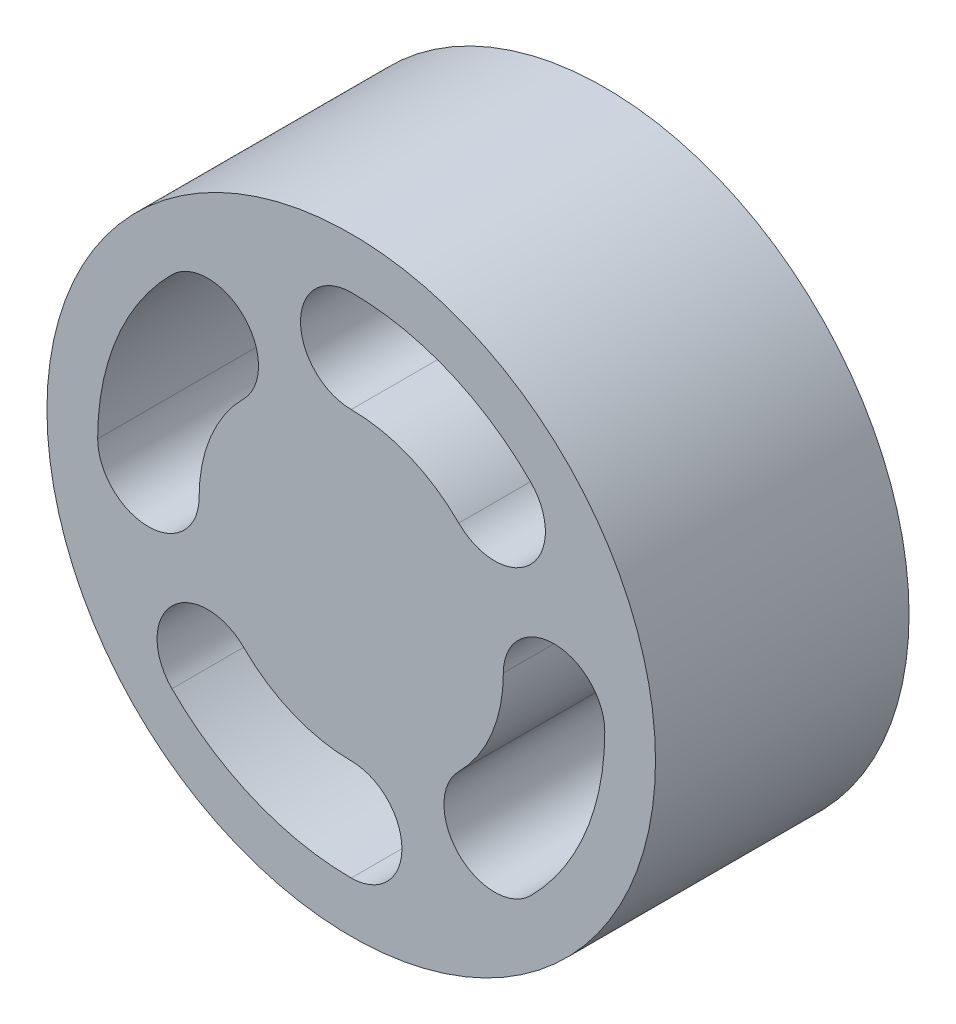
SolidWorks part; units mm, degrees
ref_plane "前视基准面" through (0, 0, 0) normal (0, 0, 1) x (1, 0, 0)
ref_plane "上视基准面" through (0, 0, 0) normal (0, 1, 0) x (1, 0, 0)
ref_plane "右视基准面" through (0, 0, 0) normal (1, 0, 0) x (0, 0, -1)
other "Configuration Table"
sketch "草图1" plane through (0, 0, 0) normal (0, 0, 1) x (1, 0, 0)
  circle A0 centre (0, 0) radius 30
  dimension "D1" = 60
extrude "凸台-拉伸1" add sketch "草图1" along normal blind 25
sketch "草图2" plane through (0, 0, 0) normal (0, 0, 1) x (1, 0, 0)
  line L0 (0, 0) -> (0, 1.4)
  line L1 (-1000, 1.4) -> (49000, 1.4)
  circle A0 centre (0, 0) radius 2
  circle A1 centre (0, 0) radius 3
  dimension "D1" = 4
  dimension "D2" = 6
  dimension "D3" = 1.4
extrude "凸台-拉伸5" add sketch "草图2" against normal blind 10 contours L1 A1 A0 | L1 A1 A0 | L1 A0
ref_plane "基准面1" through (0, 3, 0) normal (0, 1, 0) x (1, 0, 0)
sketch "草图4" plane through (0, 3, 0) normal (0, 1, 0) x (1, 0, 0)
  line L0 (-1.4283, 10) -> (1.4283, 10) construction
  circle A0 centre (0, 7) radius 1
  dimension "D1" = 2
  dimension "D2" = 3
extrude "切除-拉伸1" cut sketch "草图4" against normal up to next
sketch "草图6" plane through (0, 0, 0) normal (0, 0, -1) x (-1, 0, 0)
  line L0 (19.25, 3) -> (-19.25, 3) construction
  line L1 (-3, -3) -> (3, -3)
  line L2 (-3, -3) -> (-3, 3)
  line L3 (-3, 3) -> (3, 3)
  line L4 (3, -3) -> (3, 3)
  line L5 (-3, -3) -> (3, 3) construction
  line L6 (-3, 3) -> (3, -3) construction
  line L7 (7, -7) -> (7, 7)
  line L8 (-7, 7) -> (7, 7)
  line L9 (-7, -7) -> (-7, 7)
  line L10 (-7, -7) -> (7, -7)
  line L11 (0, 0) -> (0, 25)
  circle A1 centre (0, 0) radius 15
  circle A3 centre (0, 0) radius 25
  circle A4 centre (0, 0) radius 20
  circle A5 centre (0, 20) radius 5
  circle A6 centre (14.1421, 14.1421) radius 5
  circle A7 centre (20, 0) radius 5
  circle A8 centre (14.1421, -14.1421) radius 5
  circle A9 centre (0, -20) radius 5
  circle A10 centre (-14.1421, -14.1421) radius 5
  circle A11 centre (-20, 0) radius 5
  circle A12 centre (-14.1421, 14.1421) radius 5
  point P0 (0, 0)
  point P38 (0, 0)
  dimension "D3" = 30
  dimension "D4" = 10
  dimension "D6" = 8
  dimension "D1" = 6
  dimension "D2" = 4
  dimension "D5" = 5
extrude "切除-拉伸3" cut sketch "草图6" against normal up to next contours A11 A3 A10 A4 | A11 A4 A10 A1 | A11 A4 | A4 A11 | A4 A10 | A10 A4 | A4 A9 | A4 A9 | A9 A3 A8 A4 | A9 A4 A8 A1 | A4 A8 | A4 A8 | A7 A4 | A4 A7 | A7 A3 A6 A4 | A7 A4 A6 A1 | A4 A6 | A6 A4 | L11 A5 A4 | A4 A5 L11 | L11 A5 A4 | A4 A5 L11 | A12 A1 A5 A4 | A12 A4 A5 A3 | A4 A12 | A4 A12
